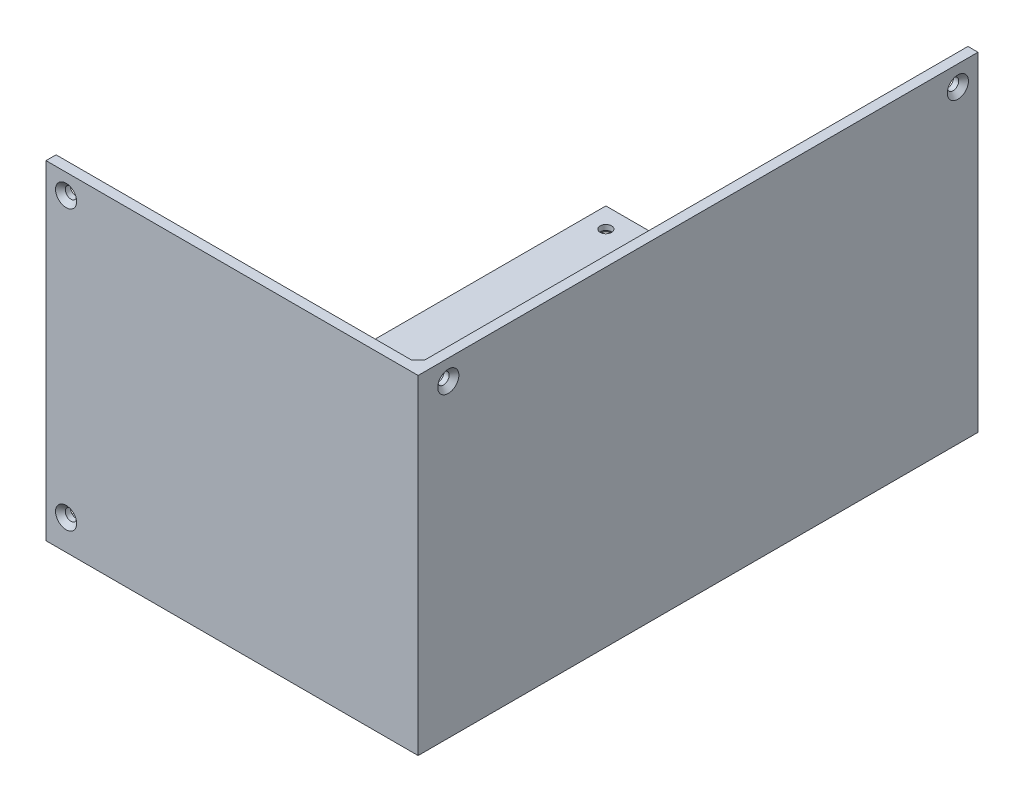
SolidWorks part; units mm, degrees
ref_plane "Front Plane" through (0, 0, 0) normal (0, 0, 1) x (1, 0, 0)
ref_plane "Top Plane" through (0, 0, 0) normal (0, 1, 0) x (1, 0, 0)
ref_plane "Right Plane" through (0, 0, 0) normal (1, 0, 0) x (0, 0, -1)
sketch "Sketch2" plane through (0, 0, 0) normal (0, 0, 1) x (1, 0, 0)
  line L0 (-3, -37) -> (-3, 58.2) construction
  line L1 (-3, -37) -> (3, -37) construction
  line L2 (-3, -37) -> (105, -37)
  line L3 (-3, -37) -> (-3, 58.2)
  line L4 (-3, 58.2) -> (105, 58.2)
  line L5 (105, -37) -> (105, 58.2)
extrude "Boss-Extrude1" add sketch "Sketch2" along normal blind 3
sketch "Sketch3" plane through (105, 0, 0) normal (1, 0, 0) x (0, 0, -1)
  line L1 (-3, 58.2) -> (164, 58.2)
  line L2 (-3, 58.2) -> (-3, -37)
  line L3 (-3, -37) -> (164, -37)
  line L4 (164, 58.2) -> (164, -37)
extrude "Boss-Extrude2" add sketch "Sketch3" along normal blind 3
sketch "Sketch4" plane through (0, -37, 0) normal (0, -1, 0) x (1, 0, 0)
  line L1 (108, -164) -> (-3, -164)
  line L2 (108, -164) -> (108, 3)
  line L3 (108, 3) -> (-3, 3)
  line L4 (-3, -164) -> (-3, 3)
extrude "Boss-Extrude3" add sketch "Sketch4" along normal blind 3
sketch "Sketch5" plane through (0, 0, 3) normal (0, 0, 1) x (1, 0, 0)
  point P0 (3, -31)
  point P1 (3, 52.2)
hole_wizard "CSK for M3 Flat Head Machine Screw1" positions "Sketch5" profile "Sketch6" countersink size "M3" standard "ANSI Metric" end condition up to next
sketch "Sketch6" plane through (3, -31, 3) normal (1, 0, 0) x (0, -1, 0)
  line L0 (0, 0) -> (0, 3)
  line L1 (0, 3) -> (1.7, 3)
  line L2 (1.7, 3) -> (1.7, 1.45)
  line L3 (1.7, 1.45) -> (3.15, 0)
  line L5 (3.15, 0) -> (0, 0)
  line L6 (-1.7, 1.45) -> (-3.15, 0) construction
  line L11 (0, -6.35) -> (0, 107.95) construction
  dimension "Thru Hole Dia." = 3.4
  dimension "Thru Hole Depth" = 3
  dimension "Near C'Sink Dia." = 6.3
  dimension "Near C'Sink Angle" = 90
sketch "Sketch7" plane through (0, -40, 0) normal (0, -1, 0) x (1, 0, 0)
  point P0 (3, -158)
  point P1 (99, -158)
hole_wizard "CSK for M3 Flat Head Machine Screw2" positions "Sketch7" profile "Sketch8" countersink size "M3" standard "ANSI Metric" end condition up to next
sketch "Sketch8" plane through (3, -40, -158) normal (1, 0, 0) x (0, 0, -1)
  line L0 (0, 0) -> (0, 3)
  line L1 (0, 3) -> (1.7, 3)
  line L2 (1.7, 3) -> (1.7, 1.45)
  line L3 (1.7, 1.45) -> (3.15, 0)
  line L5 (3.15, 0) -> (0, 0)
  line L6 (-1.7, 1.45) -> (-3.15, 0) construction
  line L11 (0, -6.35) -> (0, 107.95) construction
  dimension "Thru Hole Dia." = 3.4
  dimension "Thru Hole Depth" = 3
  dimension "Near C'Sink Dia." = 6.3
  dimension "Near C'Sink Angle" = 90
sketch "Sketch9" plane through (108, 0, 0) normal (1, 0, 0) x (0, 0, -1)
  point P0 (6, 52.2)
  point P1 (158, 52.2)
hole_wizard "CSK for M3 Flat Head Machine Screw3" positions "Sketch9" profile "Sketch10" countersink size "M3" standard "ANSI Metric" end condition up to next
sketch "Sketch10" plane through (108, 52.2, -6) normal (0, 1, 0) x (0, 0, -1)
  line L0 (0, 0) -> (0, 3)
  line L1 (0, 3) -> (1.7, 3)
  line L2 (1.7, 3) -> (1.7, 1.45)
  line L3 (1.7, 1.45) -> (3.15, 0)
  line L5 (3.15, 0) -> (0, 0)
  line L6 (-1.7, 1.45) -> (-3.15, 0) construction
  line L11 (0, -6.35) -> (0, 107.95) construction
  dimension "Thru Hole Dia." = 3.4
  dimension "Thru Hole Depth" = 3
  dimension "Near C'Sink Dia." = 6.3
  dimension "Near C'Sink Angle" = 90
sketch "Sketch12" plane through (0, -40, 0) normal (0, -1, 0) x (1, 0, 0)
  line L0 (44.5, -9.5) -> (44.5, -21.5) construction
  line L1 (38, -9.5) -> (44.5, -9.5) construction
  line L2 (38, -21.5) -> (38, -9.5) construction
  line L3 (44.5, -21.5) -> (38, -21.5) construction
  line L4 (89.6, -9.5) -> (89.6, -25.5) construction
  line L5 (83.4, -9.5) -> (89.6, -9.5) construction
  line L6 (83.4, -25.5) -> (83.4, -9.5) construction
  line L7 (89.6, -25.5) -> (83.4, -25.5) construction
  line L8 (89.6, -135.5) -> (83.4, -135.5) construction
  line L9 (89.6, -151.5) -> (89.6, -135.5) construction
  line L10 (83.4, -151.5) -> (89.6, -151.5) construction
  line L11 (83.4, -135.5) -> (83.4, -151.5) construction
  line L12 (44.5, -139.5) -> (38, -139.5) construction
  line L13 (44.5, -151.5) -> (44.5, -139.5) construction
  line L14 (38, -151.5) -> (44.5, -151.5) construction
  line L15 (38, -139.5) -> (38, -151.5) construction
  line L16 (44.5, -9.5) -> (44.5, -21.5)
  line L17 (38, -9.5) -> (44.5, -9.5)
  line L18 (38, -21.5) -> (38, -9.5)
  line L19 (44.5, -21.5) -> (38, -21.5)
  line L20 (89.6, -9.5) -> (89.6, -25.5)
  line L21 (83.4, -9.5) -> (89.6, -9.5)
  line L22 (83.4, -25.5) -> (83.4, -9.5)
  line L23 (89.6, -25.5) -> (83.4, -25.5)
  line L24 (89.6, -135.5) -> (83.4, -135.5)
  line L25 (89.6, -151.5) -> (89.6, -135.5)
  line L26 (83.4, -151.5) -> (89.6, -151.5)
  line L27 (83.4, -135.5) -> (83.4, -151.5)
  line L28 (44.5, -139.5) -> (38, -139.5)
  line L29 (44.5, -151.5) -> (44.5, -139.5)
  line L30 (38, -151.5) -> (44.5, -151.5)
  line L31 (38, -139.5) -> (38, -151.5)
extrude "Cut-Extrude1" cut sketch "Sketch12" against normal up to next
fillet "Fillet1" radius 2 16 edges at (38, -38.5, -9.5) (44.5, -38.5, -9.5) (44.5, -38.5, -21.5) (38, -38.5, -21.5) (89.6, -38.5, -25.5) (83.4, -38.5, -25.5) (89.6, -38.5, -9.5) (83.4, -38.5, -9.5) (83.4, -38.5, -135.5) (83.4, -38.5, -151.5) (89.6, -38.5, -151.5) (89.6, -38.5, -135.5) (44.5, -38.5, -139.5) (44.5, -38.5, -151.5) (38, -38.5, -139.5) (38, -38.5, -151.5)
chamfer "Chamfer1" distance 2 angle 45 3 edges at (51, -37, 0) (105, 10.6, 0) (105, -37, -82)
